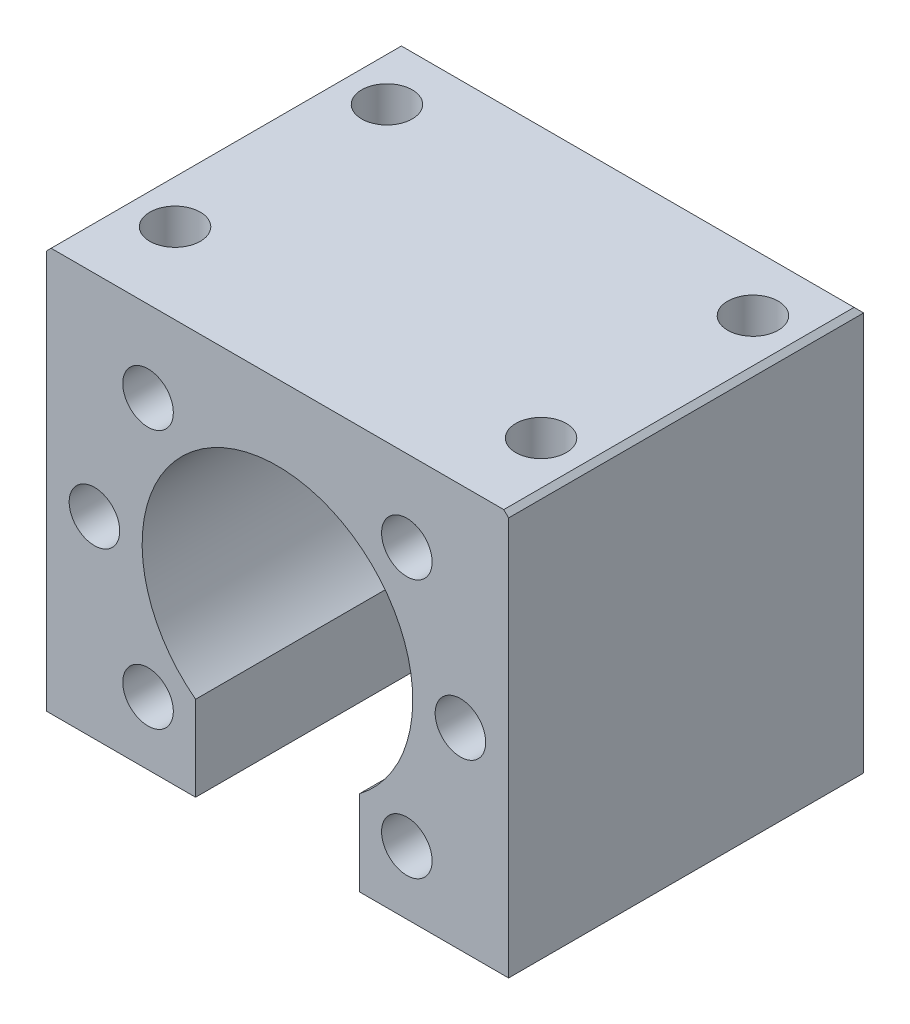
SolidWorks part; units mm, degrees
ref_plane "Front Plane" through (0, 0, 0) normal (0, 0, 1) x (1, 0, 0)
ref_plane "Top Plane" through (0, 0, 0) normal (0, 1, 0) x (1, 0, 0)
ref_plane "Right Plane" through (0, 0, 0) normal (1, 0, 0) x (0, 0, -1)
ref_plane "Plane1"
sketch "Sketch1" plane through (0, 0, 0) normal (0, 0, 1) x (1, 0, 0)
  line L0 (-24, 20) -> (24, 20)
  line L1 (24, 20) -> (24, -20)
  line L2 (24, -20) -> (8.5, -20)
  line L3 (8.5, -20) -> (8.5, -11.1872)
  line L4 (-8.5, -11.1872) -> (-8.5, -20)
  line L5 (-8.5, -20) -> (-24, -20)
  line L6 (-24, -20) -> (-24, 20)
  arc A0 (8.5, -11.1872) -> (-8.5, -11.1872) centre (0, 0) ccw
  dimension "D6" = 14.05
  dimension "D1" = 48
  dimension "D2" = 40
  dimension "D3" = 17
  dimension "D4" = 15.5
  dimension "D5" = 40
  dimension "D7" = 8.8128
extrude "Extrusion1" add sketch "Sketch1" along normal blind 36.8695
hole_wizard "Thread6" positions "Sketch3" profile "Sketch2" legacy
sketch "Sketch3" plane through (0, 0, 36.8695) normal (0, 0, 1) x (1, 0, 0)
  point P1 (-19, 0)
  point P2 (-13.435, -13.435)
  point P3 (-13.435, 13.435)
  point P4 (13.435, 13.435)
  point P5 (19, 0)
  point P6 (13.435, -13.435)
sketch "Sketch2" plane through (-19, 0, 36.8695) normal (1, 0, 0) x (0, -1, 0)
  line L0 (0, 0) -> (0, 21.5773)
  line L1 (0, 21.5773) -> (2.625, 20)
  line L2 (2.625, 20) -> (2.625, 0)
  line L4 (2.625, 0) -> (0, 0)
  line L6 (0, 21.5773) -> (-2.625, 20) construction
  line L7 (0, -4.2442) -> (0, 117.3081) construction
  dimension "Diameter" = 5.25
  dimension "Depth" = 20
  dimension "Drill Angle" = 118
hole_wizard "Thread10" positions "Sketch5" profile "Sketch4" legacy
sketch "Sketch5" plane through (0, 20, 0) normal (0, 1, 0) x (1, 0, 0)
  point P1 (-19, -6.5)
  point P2 (19, -6.5)
  point P3 (-19, -28.5)
  point P4 (19, -28.5)
sketch "Sketch4" plane through (-19, 20, 6.5) normal (1, 0, 0) x (0, 0, 1)
  line L0 (0, 0) -> (0, 17)
  line L1 (0, 17) -> (2.625, 17)
  line L2 (2.625, 17) -> (2.625, 0)
  line L3 (2.625, 0) -> (0, 0)
  line L4 (0, 110) -> (0, -10) construction
  dimension "Diameter" = 5.25
  dimension "Depth" = 17
sketch "Sketch6" plane through (0, 20, 0) normal (0, 1, 0) x (-1, 0, 0)
  line L0 (-24, 0) -> (24, 0)
  line L1 (24, 0) -> (24, 36.8695)
  line L2 (24, 36.8695) -> (-24, 36.8695)
  line L3 (-24, 36.8695) -> (-24, 0)
  circle A0 centre (19, 28.5) radius 2.625
  circle A1 centre (19, 6.5) radius 2.625
  circle A2 centre (-19, 6.5) radius 2.625
  circle A3 centre (-19, 28.5) radius 2.625
extrude "Extrusion2" add sketch "Sketch6" along normal blind 1.8695
chamfer "Chamfer1" [suppressed] distance 0.5 angle 45
chamfer "Chamfer2" distance 0.5 angle 45 3 edges at (-24, 21.8695, 18.4347) (0, 21.8695, 0) (24, 21.8695, 18.4347)
